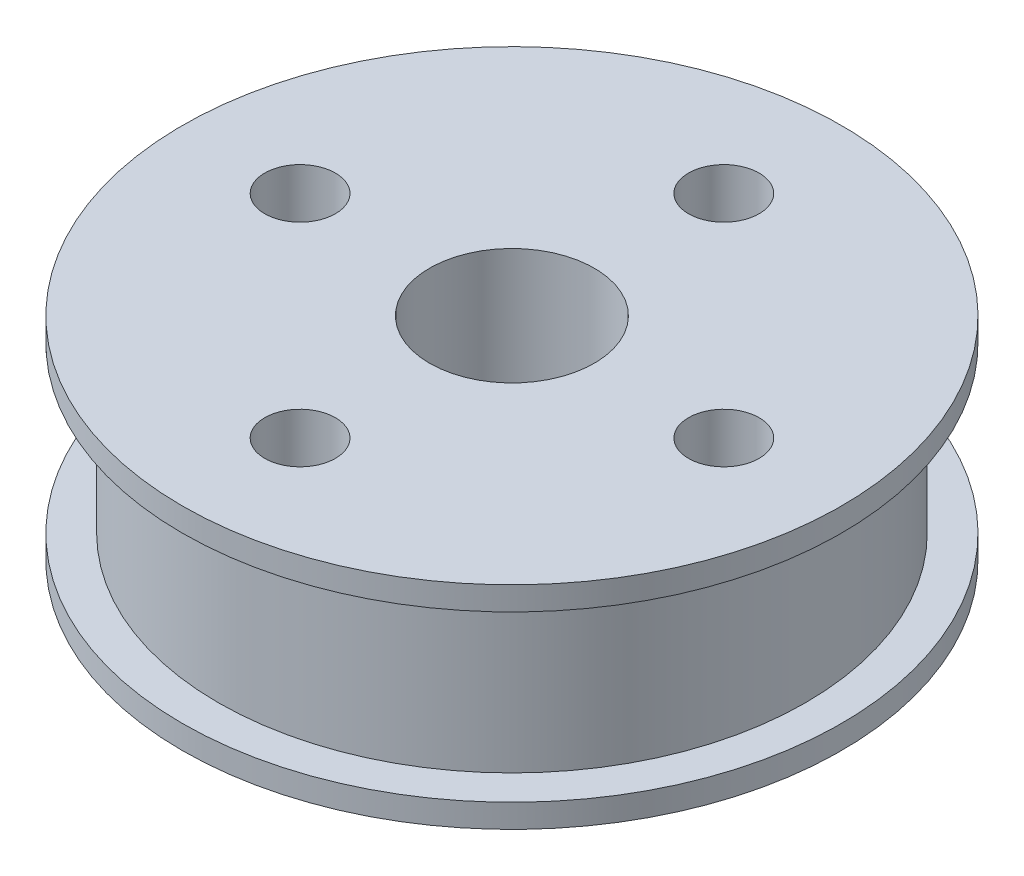
SolidWorks part; units mm, degrees
ref_plane "Front Plane" through (0, 0, 0) normal (0, 0, 1) x (1, 0, 0)
ref_plane "Top Plane" through (0, 0, 0) normal (0, 1, 0) x (1, 0, 0)
ref_plane "Right Plane" through (0, 0, 0) normal (1, 0, 0) x (0, 0, -1)
sketch "Sketch1" plane through (0, 0, 0) normal (0, 1, 0) x (1, 0, 0)
  circle A0 centre (0, 0) radius 14
  dimension "D1" = 28
extrude "Boss-Extrude1" add sketch "Sketch1" along normal blind 1
sketch "Sketch2" plane through (0, 1, 0) normal (0, 1, 0) x (1, 0, 0)
  circle A0 centre (0, 0) radius 12.475
  dimension "D1" = 24.95
extrude "Boss-Extrude2" add sketch "Sketch2" along normal blind 7
sketch "Sketch3" plane through (0, 8, 0) normal (0, 1, 0) x (1, 0, 0)
  circle A0 centre (0, 0) radius 14
  dimension "D1" = 28
extrude "Boss-Extrude3" add sketch "Sketch3" along normal blind 1
sketch "Sketch4" plane through (0, 9, 0) normal (0, 1, 0) x (1, 0, 0)
  circle A0 centre (0, 0) radius 3.5
  dimension "D1" = 7
extrude "Cut-Extrude1" cut sketch "Sketch4" against normal through all
sketch "Sketch5" plane through (0, 9, 0) normal (0, 1, 0) x (1, 0, 0)
  circle A0 centre (0, 0) radius 9 construction
  circle A1 centre (0, 9) radius 1.5
  dimension "D1" = 3
  dimension "D2" = 18
extrude "Cut-Extrude2" cut sketch "Sketch5" against normal through all
pattern_circular "CirPattern1" count 4 over 360 about axis through (0, 0, 0) along (0, 1, 0) of "Cut-Extrude2"
